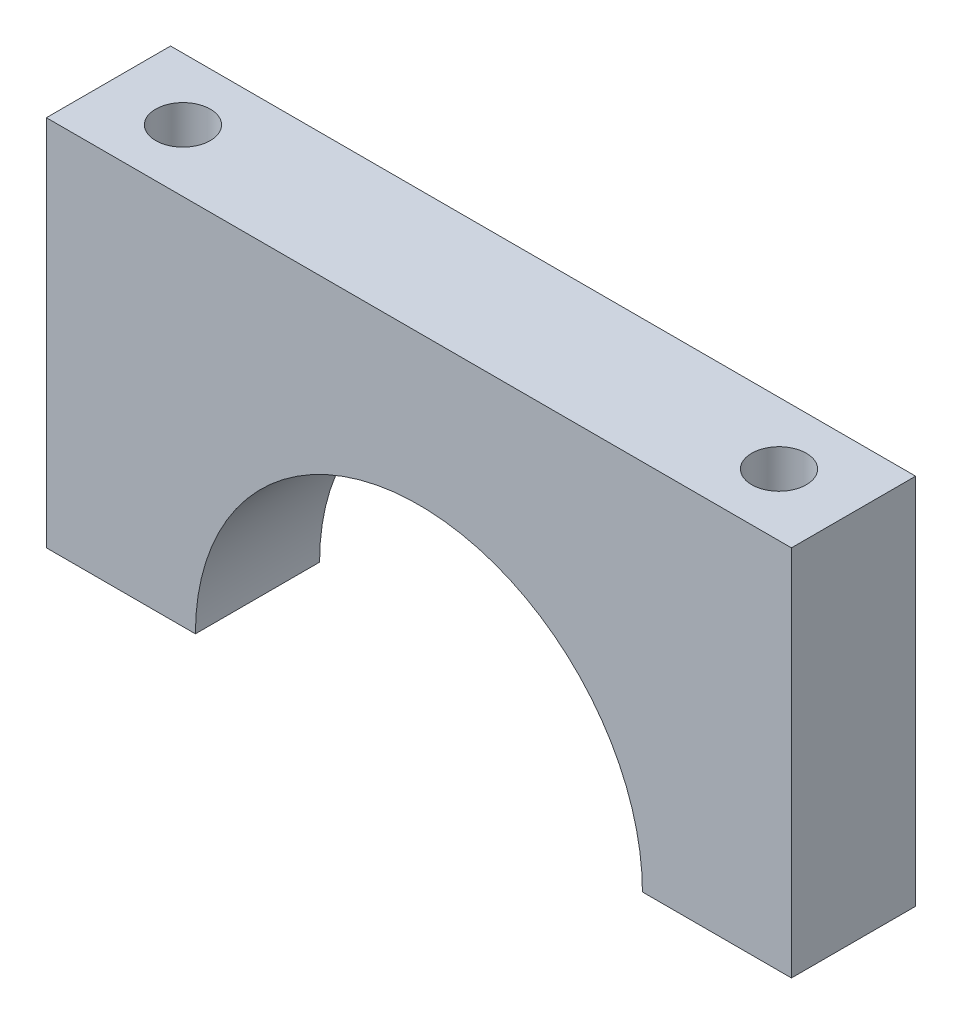
SolidWorks part; units mm, degrees
material "6061 Alloy"
ref_plane "Front Plane" through (0, 0, 0) normal (0, 0, 1) x (1, 0, 0)
ref_plane "Top Plane" through (0, 0, 0) normal (0, 1, 0) x (1, 0, 0)
ref_plane "Right Plane" through (0, 0, 0) normal (1, 0, 0) x (0, 0, -1)
sketch "Sketch1" plane through (0, 0, 0) normal (0, 0, 1) x (1, 0, 0)
  line L0 (-15, 0) -> (-9, 0)
  line L2 (-15, 0) -> (-15, 15)
  line L3 (-15, 15) -> (15, 15)
  line L4 (15, 0) -> (15, 15)
  line L5 (0, 0) -> (15, 15) construction
  line L6 (-15, 15) -> (0, 0) construction
  line L11 (0, 15) -> (0, 0) construction
  line L12 (9, 0) -> (15, 0)
  arc A0 (9, 0) -> (-9, 0) centre (0, 0) ccw
  point P0 (0, 0)
  dimension "D1" = 18
  dimension "D2" = 30
  dimension "D3" = 15
extrude "Boss-Extrude1" add sketch "Sketch1" along normal blind 5
sketch "Sketch2" plane through (0, 15, 0) normal (0, 1, 0) x (1, 0, 0)
  line L0 (-12, -2.5) -> (12, -2.5) construction
  line L1 (15, -5) -> (-15, -5) construction
  line L2 (15, 0) -> (-15, 0) construction
  line L3 (-15, -5) -> (-15, 0) construction
  line L4 (15, -5) -> (15, 0) construction
  line L6 (-9, -4) -> (9, -4) construction
  line L7 (-9, -4) -> (-9, -1) construction
  line L8 (-9, -1) -> (9, -1) construction
  line L9 (9, -4) -> (9, -1) construction
  line L10 (-9, -4) -> (9, -1) construction
  line L11 (-9, -1) -> (9, -4) construction
  circle A0 centre (-12, -2.5) radius 1.1
  circle A1 centre (12, -2.5) radius 1.1
  point P12 (0, -2.5)
  dimension "D5" = 2.2
  dimension "D1" = 3
  dimension "D2" = 3
  dimension "D3" = 18
  dimension "D4" = 3
  dimension "D6" = 24
extrude "Cut-Extrude1" cut sketch "Sketch2" against normal through all both and the other way through all
